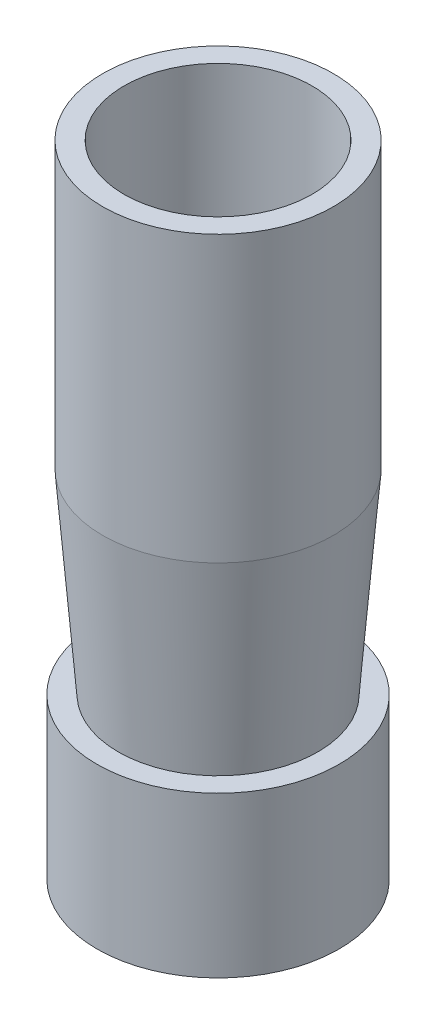
SolidWorks part; units mm, degrees
ref_plane "Front Plane" through (0, 0, 0) normal (0, 0, 1) x (1, 0, 0)
ref_plane "Top Plane" through (0, 0, 0) normal (0, 1, 0) x (1, 0, 0)
ref_plane "Right Plane" through (0, 0, 0) normal (1, 0, 0) x (0, 0, -1)
sketch "Sketch1" plane through (0, 0, 0) normal (0, 0, 1) x (1, 0, 0)
  line L1 (-23.6121, 23.103) -> (-23.6121, 16.3263)
  line L2 (-23.4347, 14.1044) -> (-21.7387, -7.1326)
  line L3 (-21.7387, -7.1326) -> (-21.7387, -16.9873)
  line L7 (-24.1496, -1.9873) -> (-25.6121, 16.3263)
  line L8 (-25.6121, 16.3263) -> (-25.6121, 26.3263)
  line L9 (-14.7971, 26.4248) -> (-14.7971, -17.3951) construction
  line L15 (-24.1496, -1.9873) -> (-26.1496, -1.9873)
  line L16 (-26.1496, -1.9873) -> (-26.1496, -16.9873)
  line L18 (-26.1496, -16.9873) -> (-21.7387, -16.9873)
  line L19 (-23.6121, 26.3263) -> (-17.5471, -12.3512)
  line L20 (-17.5471, -12.3512) -> (-17.7971, -12.552)
  line L21 (-17.7971, -12.552) -> (-23.6121, 23.103)
  line L24 (-23.6121, 16.3263) -> (-23.4347, 14.1044)
  line L25 (-25.6121, 26.3263) -> (-25.6121, 43.0163)
  line L26 (-25.6121, 43.0163) -> (-23.6121, 43.0163)
  line L27 (-23.6121, 43.0163) -> (-23.6121, 26.3263)
  point P12 (-25.6121, 21.3263)
  dimension "D1" = 2
  dimension "D2" = 10
  dimension "D3" = 2
  dimension "D4" = 90
  dimension "D5" = 90
  dimension "D6" = 2.75
  dimension "D7" = 3
  dimension "D8" = 10.815
  dimension "D9" = 2
  dimension "D10" = 90
  dimension "D11" = 16.69
revolve "Revolve1" add sketch "Sketch1" angle 360 about L9
